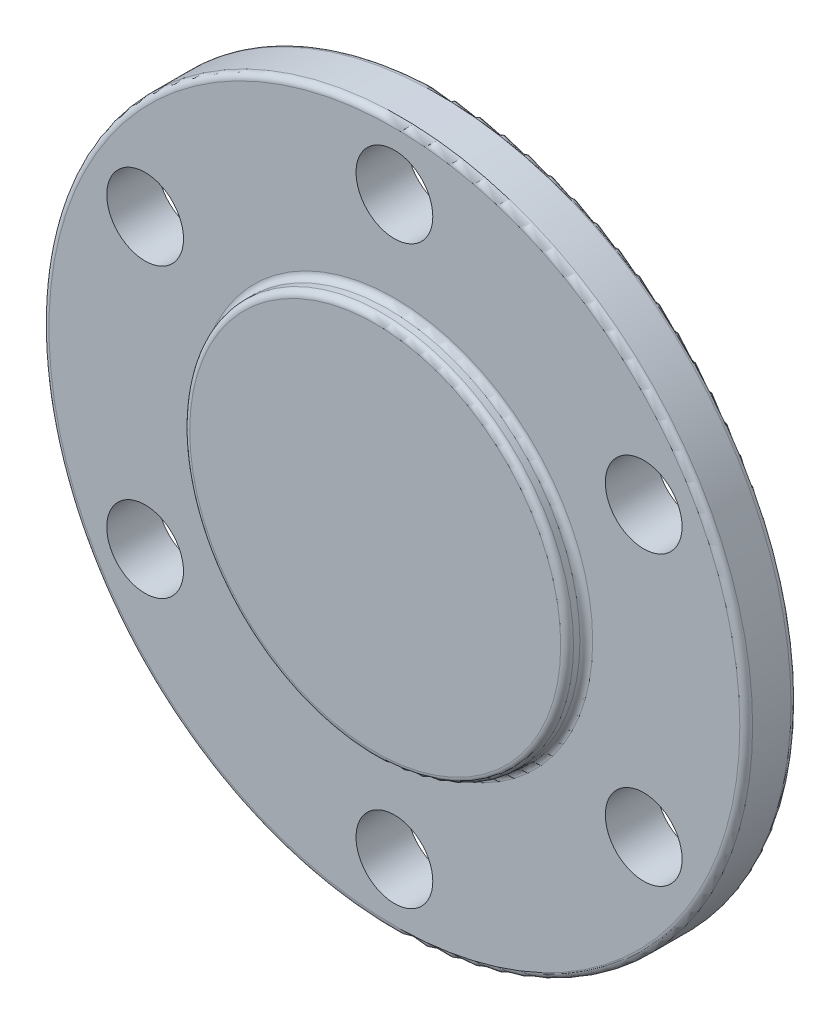
SolidWorks part; units mm, degrees
ref_plane "Front Plane" through (0, 0, 0) normal (0, 0, 1) x (1, 0, 0)
ref_plane "Top Plane" through (0, 0, 0) normal (0, 1, 0) x (1, 0, 0)
ref_plane "Right Plane" through (0, 0, 0) normal (1, 0, 0) x (0, 0, -1)
sketch "Sketch1" plane through (0, 0, 0) normal (0, 0, 1) x (1, 0, 0)
  circle A0 centre (0, 0) radius 27.5
  circle A1 centre (0, 0) radius 22.5 construction
  circle A2 centre (0, 22.5) radius 3
  circle A3 centre (19.4856, 11.25) radius 3
  circle A4 centre (19.4856, -11.25) radius 3
  circle A5 centre (0, -22.5) radius 3
  circle A6 centre (-19.4856, -11.25) radius 3
  circle A7 centre (-19.4856, 11.25) radius 3
  point P19 (0, 0)
  dimension "D1" = 55
  dimension "D2" = 45
  dimension "D3" = 6
  dimension "D4" = 6
extrude "Boss-Extrude1" add sketch "Sketch1" along normal mid plane 4
sketch "Sketch2" plane through (0, 0, 2) normal (0, 0, 1) x (1, 0, 0)
  circle A0 centre (0, 0) radius 15
  dimension "D1" = 30
extrude "Boss-Extrude2" add sketch "Sketch2" along normal blind 1.5
sketch "Sketch3" plane through (0, 0, -2) normal (0, 0, -1) x (-1, 0, 0)
  circle A0 centre (0, 0) radius 10
  dimension "D1" = 20
extrude "Boss-Extrude3" add sketch "Sketch3" along normal blind 3
fillet "Fillet1" radius 0.5 6 edges at (15, 0, 3.5) (27.5, 0, 2) (15, 0, 2) (10, 0, -2) (-10, 0, -5) (27.5, 0, -2)
